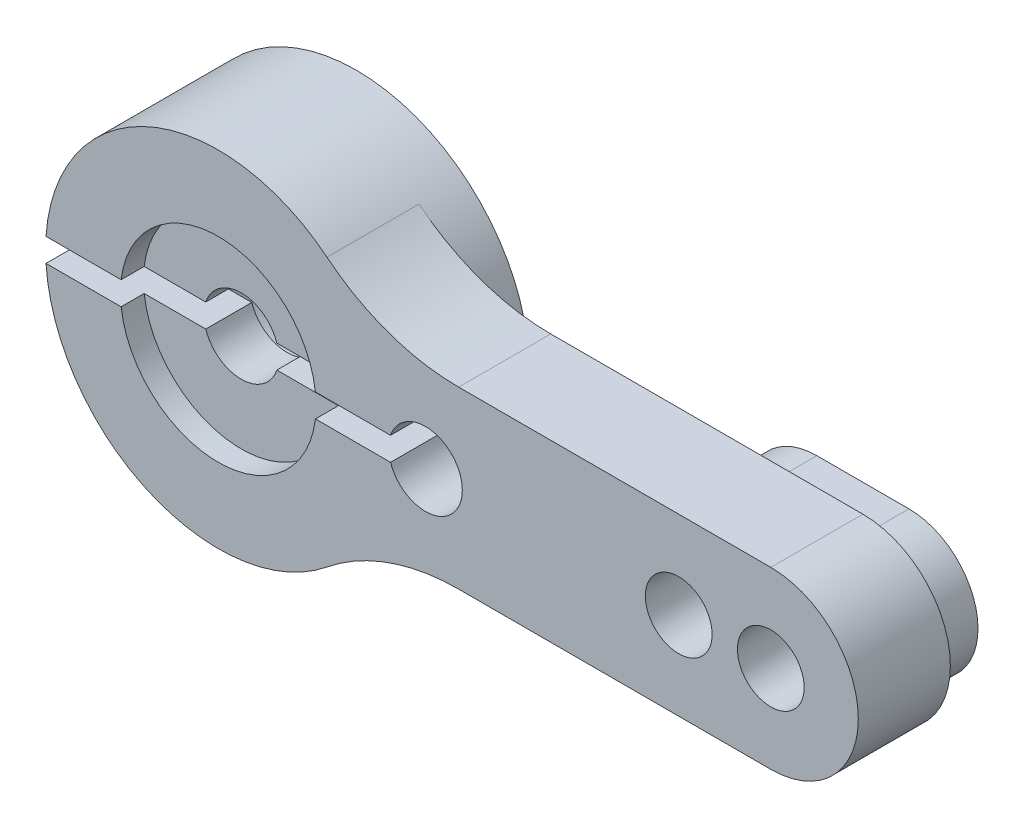
SolidWorks part; units mm, degrees
ref_plane "Front Plane" through (0, 0, 0) normal (1, 0, 0) x (0, 1, 0)
ref_plane "Top Plane" through (0, 0, 0) normal (0, 0, 1) x (0, 1, 0)
ref_plane "Right Plane" through (0, 0, 0) normal (0, 1, 0) x (-1, 0, 0)
sketch "Sketch1" plane through (0, 0, 0) normal (0, 0, 1) x (0, 1, 0)
  line L2 (-3.8, -10.4422) -> (-3.8, -24)
  line L3 (3.8, -24) -> (3.8, -10.4422)
  line L4 (-0.508, -1.5436) -> (-0.508, -7.4828)
  line L5 (0.508, -7.4828) -> (0.508, -1.5436)
  line L6 (-0.508, 1.5436) -> (-0.508, 7.4828)
  line L7 (0.508, 7.4828) -> (0.508, 1.5436)
  arc A2 (5.8268, -4.7221) -> (-5.8268, -4.7221) centre (0, 0) ccw
  arc A3 (-3.8, -24) -> (3.8, -24) centre (0, -24) ccw
  arc A4 (-3.8, -10.4422) -> (-5.8268, -4.7221) centre (-12.8852, -10.4422) ccw
  arc A5 (5.8268, -4.7221) -> (3.8, -10.4422) centre (12.8852, -10.4422) ccw
  arc A6 (-0.508, 1.5436) -> (-0.508, -1.5436) centre (0, 0) ccw
  circle A7 centre (0, -24) radius 1.45
  circle A8 centre (0, -20) radius 1.45
  arc A9 (-0.508, -7.4828) -> (0.508, -7.4828) centre (0, -9) ccw
  arc A10 (0.508, -1.5436) -> (0.508, 1.5436) centre (0, 0) ccw
  point P15 (0, -8.8975)
  point P22 (0, 0)
  point P23 (0, -8.8975)
  point P26 (0, -8.8975)
  point P27 (0, 0)
  point P28 (0, 0)
  point P29 (0, 0)
  point P30 (0, 0)
  point P31 (0.5, -7.4833)
  point P32 (0, 0)
  point P33 (-32.8539, 8.4592)
  point P34 (0, 0)
  dimension "D1" = 15
  dimension "D2" = 7.6
  dimension "D4" = 2.9
  dimension "D3" = 3.25
  dimension "D5" = 24
  dimension "D7" = 1.6
  dimension "D6" = 20
  dimension "D9" = 9
extrude "Boss-Extrude1" add sketch "Sketch1" along normal blind 4 contours A10 L5 A9 L4 A6 L6 A2 A4 L2 A3 L3 A5 L7 A8 A7
sketch "Sketch3" plane through (0, 0, 0) normal (0, 0, -1) x (1, 0, 0)
  line L0 (20, 3) -> (24, 3)
  line L1 (24, -3) -> (20, -3)
  line L2 (-7.4828, 0.508) -> (-2.8552, 0.508)
  line L3 (-1.5436, 0.508) -> (-7.4828, 0.508) construction
  line L4 (-2.8552, -0.508) -> (-7.4828, -0.508)
  line L5 (-7.4828, -0.508) -> (-1.5436, -0.508) construction
  line L6 (7.4828, 0.508) -> (2.8552, 0.508)
  line L7 (1.5436, 0.508) -> (7.4828, 0.508) construction
  line L8 (7.4828, -0.508) -> (2.8552, -0.508)
  line L9 (7.4828, -0.508) -> (1.5436, -0.508) construction
  arc A0 (-2.8552, -0.508) -> (2.8552, -0.508) centre (0, 0) ccw
  arc A1 (-7.4828, -0.508) -> (7.4828, -0.508) centre (0, 0) ccw
  arc A2 (20, 3) -> (20, -3) centre (20, 0) ccw
  arc A3 (24, -3) -> (24, 3) centre (24, 0) ccw
  arc A4 (7.4828, 0.508) -> (-7.4828, 0.508) centre (0, 0) ccw
  arc A5 (2.8552, 0.508) -> (-2.8552, 0.508) centre (0, 0) ccw
  dimension "D1" = 6
  dimension "D2" = 5.8
extrude "Boss-Extrude3" add sketch "Sketch3" along normal blind 2
sketch "Sketch4" plane through (0, 0, 4) normal (0, 0, 1) x (1, 0, 0)
  circle A0 centre (0, 0) radius 4.25
  dimension "D1" = 8.5
extrude "Cut-Extrude1" cut sketch "Sketch4" against normal blind 1
sketch "Sketch6" plane through (0, 0, 0) normal (0, 0, -1) x (1, 0, 0)
  circle A0 centre (0, 0) radius 2.9
  arc A1 (-2.8552, -0.508) -> (2.8552, -0.508) centre (0, 0) ccw construction
extrude "Cut-Extrude2" cut sketch "Sketch6" against normal blind 1
